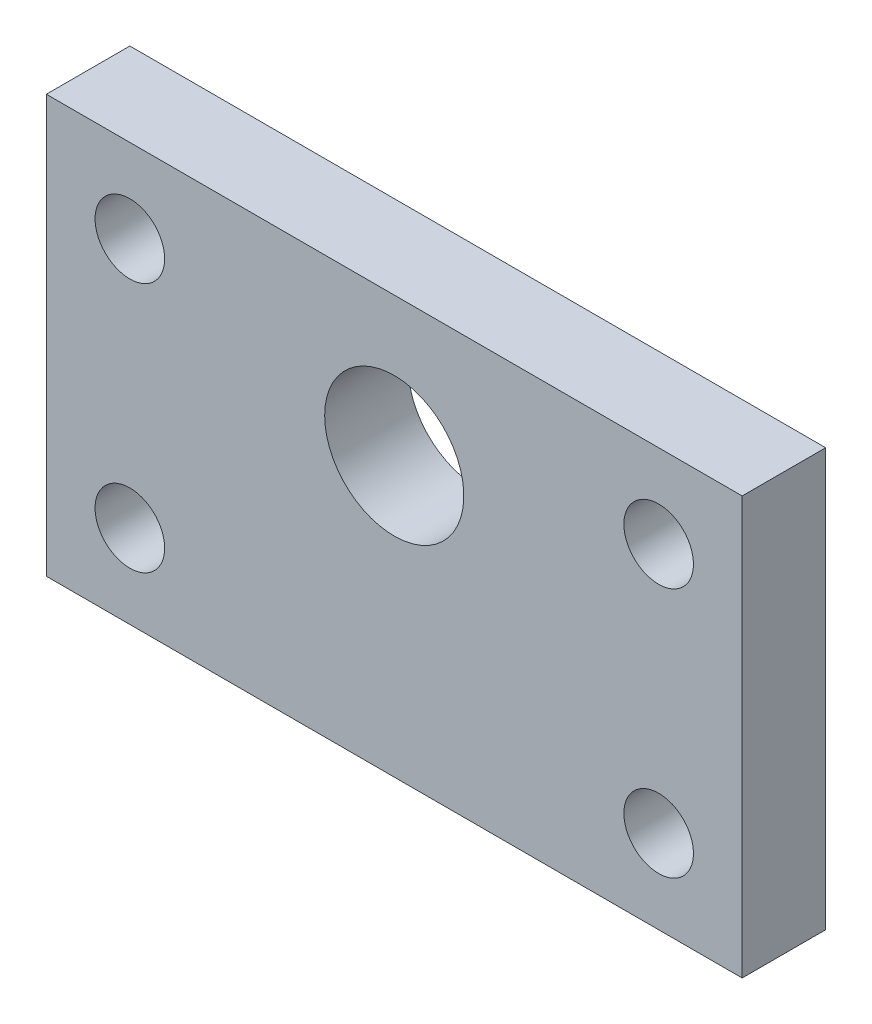
SolidWorks part; units mm, degrees
ref_plane "Front Plane" through (0, 0, 0) normal (0, 0, 1) x (1, 0, 0)
ref_plane "Top Plane" through (0, 0, 0) normal (0, 1, 0) x (1, 0, 0)
ref_plane "Right Plane" through (0, 0, 0) normal (1, 0, 0) x (0, 0, -1)
sketch "Sketch1" plane through (0, 0, 0) normal (0, 0, 1) x (1, 0, 0)
  line L0 (-186.1873, 0) -> (210.3378, 0) construction
  line L1 (-125, 75) -> (125, 75)
  line L2 (-125, 75) -> (-125, -75)
  line L3 (-125, -75) -> (125, -75)
  line L4 (125, 75) -> (125, -75)
  line L5 (0, 100.4055) -> (0, -113.3385) construction
  circle A0 centre (-95, 45) radius 12.5
  circle A1 centre (-95, -45) radius 12.5
  circle A2 centre (95, -45) radius 12.5
  circle A3 centre (95, 45) radius 12.5
  circle A5 centre (0, 25) radius 25
  point P0 (0, 0)
  dimension "D7" = 25
  dimension "D8" = 25
  dimension "D1" = 250
  dimension "D2" = 150
  dimension "D3" = 90
  dimension "D4" = 30
  dimension "D5" = 30
  dimension "D6" = 30
  dimension "D9" = 45
  dimension "D12" = 190
extrude "Boss-Extrude1" add sketch "Sketch1" along normal blind 30
